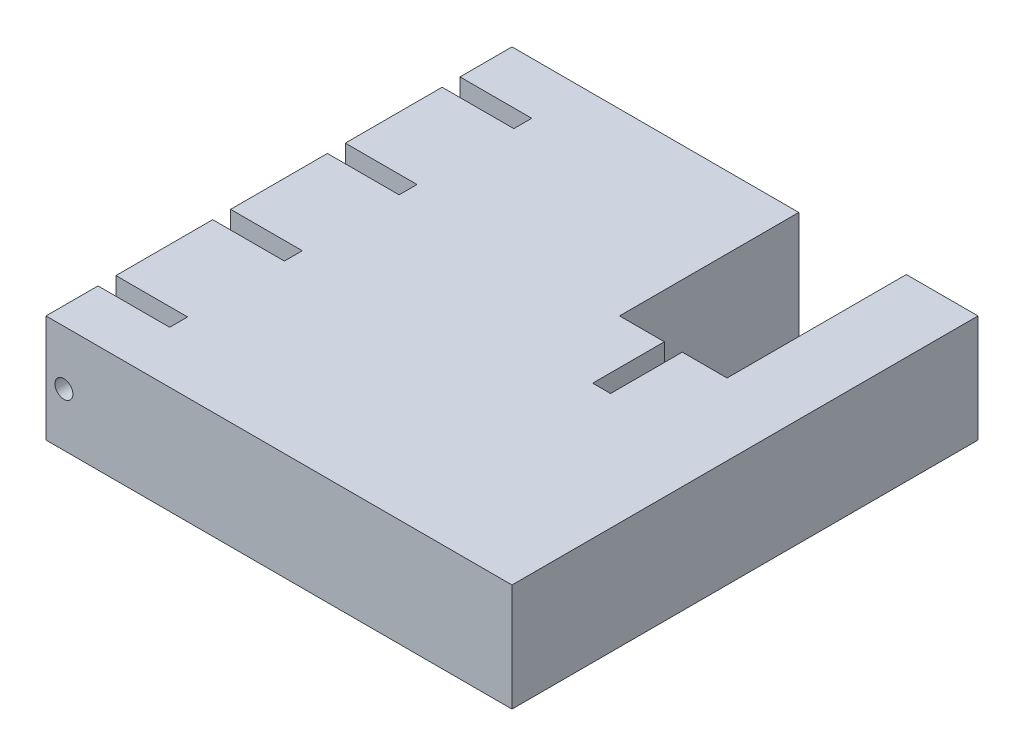
SolidWorks part; units mm, degrees
ref_plane "Front Plane" through (0, 0, 0) normal (0, 0, 1) x (1, 0, 0)
ref_plane "Top Plane" through (0, 0, 0) normal (0, 1, 0) x (1, 0, 0)
ref_plane "Right Plane" through (0, 0, 0) normal (1, 0, 0) x (0, 0, -1)
sketch "Sketch2" plane through (0, 0, 0) normal (0, 1, 0) x (1, 0, 0)
  line L1 (-113.4333, 18.1516) -> (16.5667, 18.1516)
  line L2 (-113.4333, 18.1516) -> (-113.4333, -111.8484)
  line L3 (-113.4333, -111.8484) -> (16.5667, -111.8484)
  line L4 (16.5667, 18.1516) -> (16.5667, -111.8484)
  dimension "D1" = 130
  dimension "D2" = 130
extrude "Boss-Extrude1" add sketch "Sketch2" along normal blind 30
sketch "Sketch3" plane through (0, 30, 0) normal (0, 1, 0) x (1, 0, 0)
  line L0 (-113.4333, 18.1516) -> (-113.4333, -111.8484) construction
  line L1 (-113.4333, 3.6516) -> (-93.4333, 3.6516)
  line L2 (-113.4333, 3.6516) -> (-113.4333, -1.3484)
  line L3 (-113.4333, -1.3484) -> (-93.4333, -1.3484)
  line L4 (-93.4333, 3.6516) -> (-93.4333, -1.3484)
  line L5 (16.5667, 18.1516) -> (-113.4333, 18.1516) construction
  dimension "D1" = 20
  dimension "D2" = 5
  dimension "D3" = 14.5
extrude "Cut-Extrude1" cut sketch "Sketch3" against normal through all and the other way through all
sketch "Sketch8" plane through (0, 30, 0) normal (0, 1, 0) x (1, 0, 0)
  line L0 (-113.4333, -1.3484) -> (-113.4333, -111.8484) construction
  line L1 (-113.4333, -28.3484) -> (-93.4333, -28.3484)
  line L2 (-113.4333, -28.3484) -> (-113.4333, -33.3484)
  line L3 (-113.4333, -33.3484) -> (-93.4333, -33.3484)
  line L4 (-93.4333, -28.3484) -> (-93.4333, -33.3484)
  line L5 (16.5667, 18.1516) -> (-113.4333, 18.1516) construction
  line L6 (-113.4333, -60.3484) -> (-93.4333, -60.3484)
  line L7 (-113.4333, -60.3484) -> (-113.4333, -65.3484)
  line L8 (-113.4333, -65.3484) -> (-93.4333, -65.3484)
  line L9 (-93.4333, -60.3484) -> (-93.4333, -65.3484)
  line L10 (-113.4333, -92.3484) -> (-93.4333, -92.3484)
  line L11 (-113.4333, -92.3484) -> (-113.4333, -97.3484)
  line L12 (-113.4333, -97.3484) -> (-93.4333, -97.3484)
  line L13 (-93.4333, -92.3484) -> (-93.4333, -97.3484)
  dimension "D1" = 20
  dimension "D2" = 5
  dimension "D3" = 20
  dimension "D4" = 5
  dimension "D5" = 20
  dimension "D6" = 5
  dimension "D7" = 46.5
  dimension "D8" = 78.5
  dimension "D9" = 110.5
extrude "Cut-Extrude2" cut sketch "Sketch8" against normal through all and the other way through all
sketch "Sketch9" plane through (0, 0, 111.8484) normal (0, 0, 1) x (1, 0, 0)
  line L0 (-113.4333, 30) -> (-113.4333, 0) construction
  circle A0 centre (-108.4333, 14.8465) radius 2.5
  dimension "D1" = 5
  dimension "D2" = 5
extrude "Cut-Extrude3" cut sketch "Sketch9" against normal through all and the other way through all
sketch "Sketch10" plane through (0, 30, 0) normal (0, 1, 0) x (1, 0, 0)
  line L0 (16.5667, 18.1516) -> (-113.4333, 18.1516) construction
  line L1 (-33.4333, 18.1516) -> (-3.4333, 18.1516)
  line L2 (-33.4333, 18.1516) -> (-33.4333, -31.8484)
  line L3 (-33.4333, -31.8484) -> (-3.4333, -31.8484)
  line L4 (-3.4333, 18.1516) -> (-3.4333, -31.8484)
  line L5 (16.5667, -111.8484) -> (16.5667, 18.1516) construction
  dimension "D1" = 30
  dimension "D2" = 50
  dimension "D3" = 0
  dimension "D4" = 20
extrude "Cut-Extrude4" cut sketch "Sketch10" against normal through all and the other way through all
sketch "Sketch12" plane through (0, 30, 0) normal (0, 1, 0) x (1, 0, 0)
  line L0 (-33.4333, -31.8484) -> (-3.4333, -31.8484) construction
  line L1 (-15.9333, -51.8484) -> (-20.9333, -51.8484)
  line L2 (-15.9333, -51.8484) -> (-15.9333, -31.8484)
  line L3 (-15.9333, -31.8484) -> (-20.9333, -31.8484)
  line L4 (-20.9333, -51.8484) -> (-20.9333, -31.8484)
  line L5 (-33.4333, 18.1516) -> (-33.4333, -31.8484) construction
  dimension "D1" = 5
  dimension "D2" = 20
  dimension "D3" = 12.5
extrude "Cut-Extrude5" cut sketch "Sketch12" against normal through all and the other way through all
sketch "Sketch13" plane through (-20.9333, 0, 0) normal (1, 0, 0) x (0, 0, -1)
  line L0 (-51.8484, 0) -> (-51.8484, 30) construction
  circle A0 centre (-46.8484, 12.7743) radius 2.5
  dimension "D1" = 5
  dimension "D2" = 5
extrude "Cut-Extrude6" cut sketch "Sketch13" against normal blind 10 and the other way blind 10
